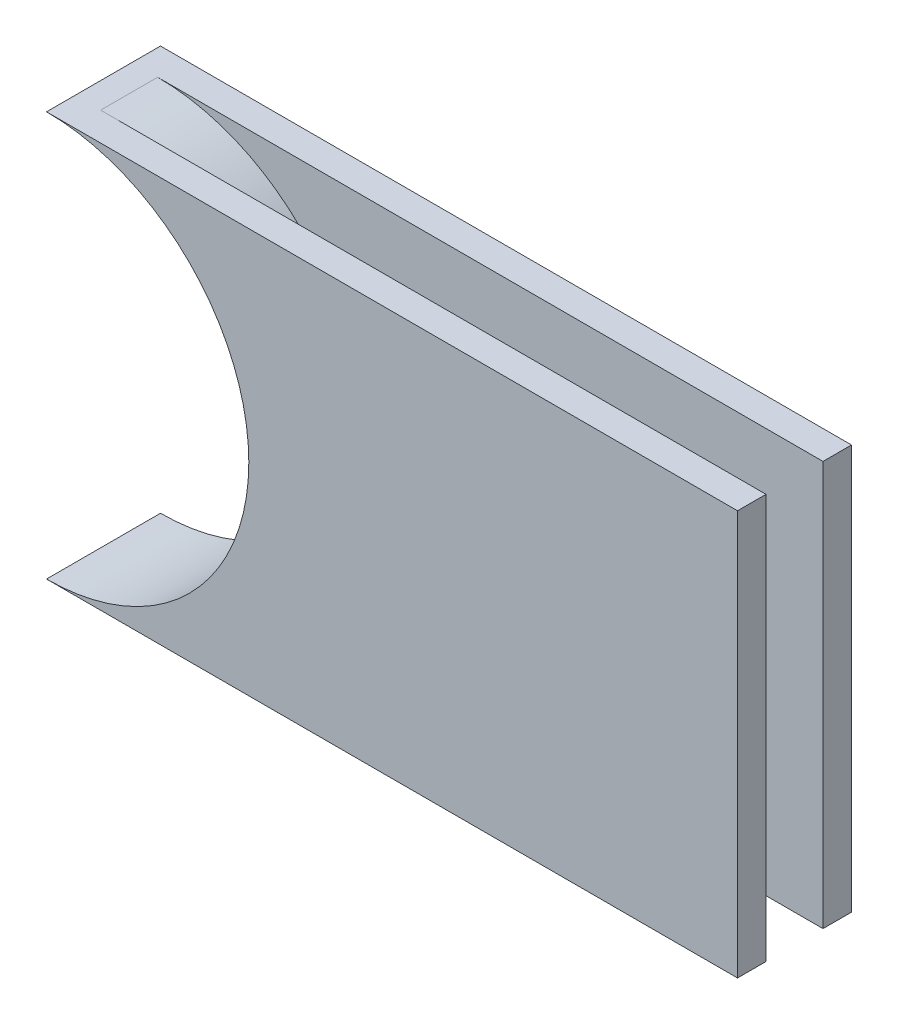
SolidWorks part; units mm, degrees
ref_plane "Front Plane" through (0, 0, 0) normal (0, 0, 1) x (1, 0, 0)
ref_plane "Top Plane" through (0, 0, 0) normal (0, 1, 0) x (1, 0, 0)
ref_plane "Right Plane" through (0, 0, 0) normal (1, 0, 0) x (0, 0, -1)
sketch "Sketch1" plane through (0, 0, 0) normal (0, 0, 1) x (1, 0, 0)
  circle A0 centre (0, 0) radius 19.939
  dimension "D1" = 39.878
extrude "circle extrude" add sketch "Sketch1" along normal blind 7.62
sketch "Sketch3" plane through (0, 0, 0) normal (1, 0, 0) x (0, 0, -1)
  line L0 (0, 55) -> (0, -55) construction
  line L1 (-7.62, 19.939) -> (0, 19.939)
  line L2 (-7.62, 19.939) -> (-7.62, -19.939)
  line L3 (-7.62, -19.939) -> (0, -19.939)
  line L4 (0, 19.939) -> (0, -19.939)
  line L5 (-7.62, -19.939) -> (0, -19.939) construction
extrude "rectangle extrude" add sketch "Sketch3" along normal blind 63.5
sketch "Sketch2" plane through (0, 0, 7.62) normal (0, 0, 1) x (1, 0, 0)
  circle A0 centre (0, 0) radius 18.034
  dimension "D1" = 36.068
extrude "cricle cut" cut sketch "Sketch2" against normal through all
sketch "Sketch4" plane through (0, 0, 7.62) normal (0, 0, 1) x (1, 0, 0)
  line L0 (63.5, 19.939) -> (63.5, -19.939) construction
  line L1 (0, 18.034) -> (61.595, 18.034)
  line L2 (0, 18.034) -> (0, -18.034)
  line L3 (0, -18.034) -> (61.595, -18.034)
  line L4 (61.595, 18.034) -> (61.595, -18.034)
  line L5 (63.5, -19.939) -> (0, -19.939) construction
  circle A0 centre (0, 0) radius 18.034 construction
  point P4 (0, 0)
  dimension "D1" = 1.905
  dimension "D2" = 1.905
extrude "frame cut" cut sketch "Sketch4" against normal through all flip side to cut
sketch "Sketch8" plane through (0, 0, 7.62) normal (0, 0, 1) x (1, 0, 0)
  line L6 (0, -18.034) -> (61.595, -18.034) construction
  line L7 (36.068, 18.034) -> (61.595, 18.034)
  line L8 (61.595, 18.034) -> (61.595, -18.034)
  line L9 (61.595, -18.034) -> (36.068, -18.034)
  line L10 (61.595, 18.034) -> (0, 18.034) construction
  arc A1 (36.068, -18.034) -> (36.068, 18.034) centre (36.068, 0) ccw
  point P1 (0, 0)
  point P3 (0, 0)
  dimension "D1" = 36.068
extrude "end cut" [suppressed] cut sketch "Sketch8" against normal through all
sketch "Sketch10" plane through (0, 0, 0) normal (0, 0, -1) x (-1, 0, 0)
  line L2 (0, 18.034) -> (-61.595, 18.034)
  line L3 (-61.595, -18.034) -> (0, -18.034)
  line L4 (0, 18.034) -> (-61.595, 18.034)
  line L5 (-61.595, -18.034) -> (0, -18.034)
  line L7 (-61.595, 18.034) -> (-61.595, -18.034)
  line L8 (-61.595, 18.034) -> (-61.595, -18.034)
  arc A3 (0, 18.034) -> (0, -18.034) centre (0, 0) ccw
  arc A5 (0, 18.034) -> (0, -18.034) centre (0, 0) ccw
  dimension "D1" = 0
extrude "extension" add sketch "Sketch10" along normal blind 2.54
ref_plane "Plane2" through (20.32, 0, 0) normal (1, 0, 0) x (0, 0, -1)
sketch "Sketch11" plane through (20.32, 0, 0) normal (1, 0, 0) x (0, 0, -1)
  line L0 (2.54, 18.034) -> (-7.62, 18.034) construction
  line L1 (0, -18.034) -> (-5.08, -18.034)
  line L2 (0, -18.034) -> (0, 18.034)
  line L3 (0, 18.034) -> (-5.08, 18.034)
  line L4 (-5.08, -18.034) -> (-5.08, 18.034)
  line L5 (0, -18.034) -> (-5.08, 18.034) construction
  line L6 (0, 18.034) -> (-5.08, -18.034) construction
  line L7 (2.54, -18.034) -> (-7.62, -18.034) construction
  point P0 (-2.54, 0)
  point P7 (-0.3296, -14.9993)
  dimension "D1" = 2.54
  dimension "D2" = 5.08
extrude "middle" cut sketch "Sketch11" along normal through all
sketch "Sketch12" plane through (0, 0, 0) normal (0, 0, 1) x (1, 0, 0)
  line L0 (20.32, -5.588) -> (20.32, 5.588) construction
  line L1 (0, 18.034) -> (61.595, 18.034) construction
  line L2 (2.286, 18.034) -> (0, 18.034)
  line L3 (0, 18.034) -> (0, -18.034)
  line L4 (0, -18.034) -> (2.286, -18.034)
  arc A0 (2.286, -18.034) -> (2.286, 18.034) centre (2.286, 0) ccw
  dimension "D1" = 36.068
extrude "circle extension" cut sketch "Sketch12" along normal blind 5.08 flip side to cut
